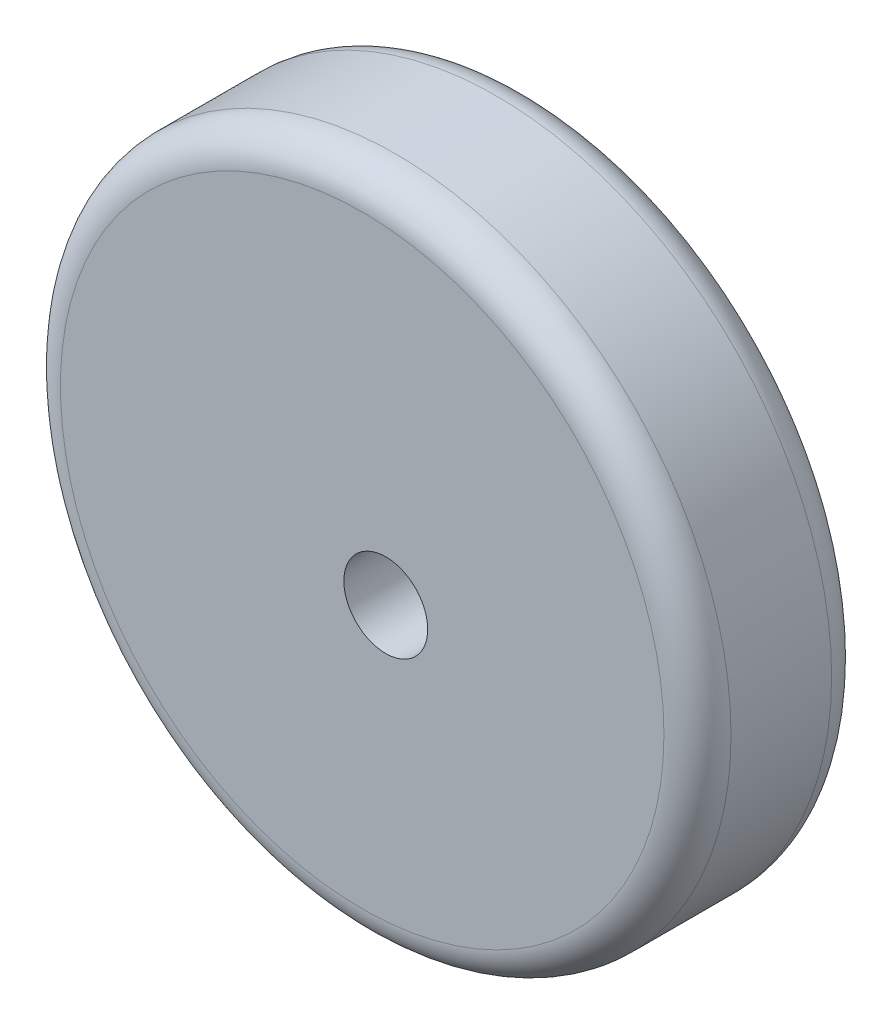
SolidWorks part; units mm, degrees
ref_plane "Front Plane" through (0, 0, 0) normal (0, 0, 1) x (1, 0, 0)
ref_plane "Top Plane" through (0, 0, 0) normal (0, 1, 0) x (1, 0, 0)
ref_plane "Right Plane" through (0, 0, 0) normal (1, 0, 0) x (0, 0, -1)
sketch "Sketch1" plane through (0, 0, 0) normal (0, 0, 1) x (1, 0, 0)
  circle A0 centre (-30.291, 15.9182) radius 25.4
  dimension "D1" = 50.8
extrude "Boss-Extrude1" add sketch "Sketch1" along normal blind 12.7 contours A0
fillet "Fillet1" radius 2.54 1 edges at (-4.891, 15.9182, 12.7)
fillet "Fillet2" radius 2.54 1 edges at (-4.891, 15.9182, 0)
hole_wizard "1/4 (0.25) Diameter Hole1" positions "Sketch4" profile "Sketch3" hole size "1/4" standard "ANSI Inch" end condition through all
sketch "Sketch4" plane through (0, 0, 0) normal (0, 0, -1) x (-1, 0, 0)
  point P0 (28.5014, 13.8745)
sketch "Sketch3" plane through (-28.5014, 13.8745, 0) normal (1, 0, 0) x (0, 1, 0)
  line L0 (0, 0) -> (0, 12.7)
  line L1 (0, 12.7) -> (3.175, 12.7)
  line L2 (3.175, 12.7) -> (3.175, 0)
  line L5 (3.175, 0) -> (0, 0)
  line L11 (0, -6.35) -> (0, 107.95) construction
  dimension "Thru Hole Dia." = 6.35
  dimension "Thru Hole Depth" = 12.7
